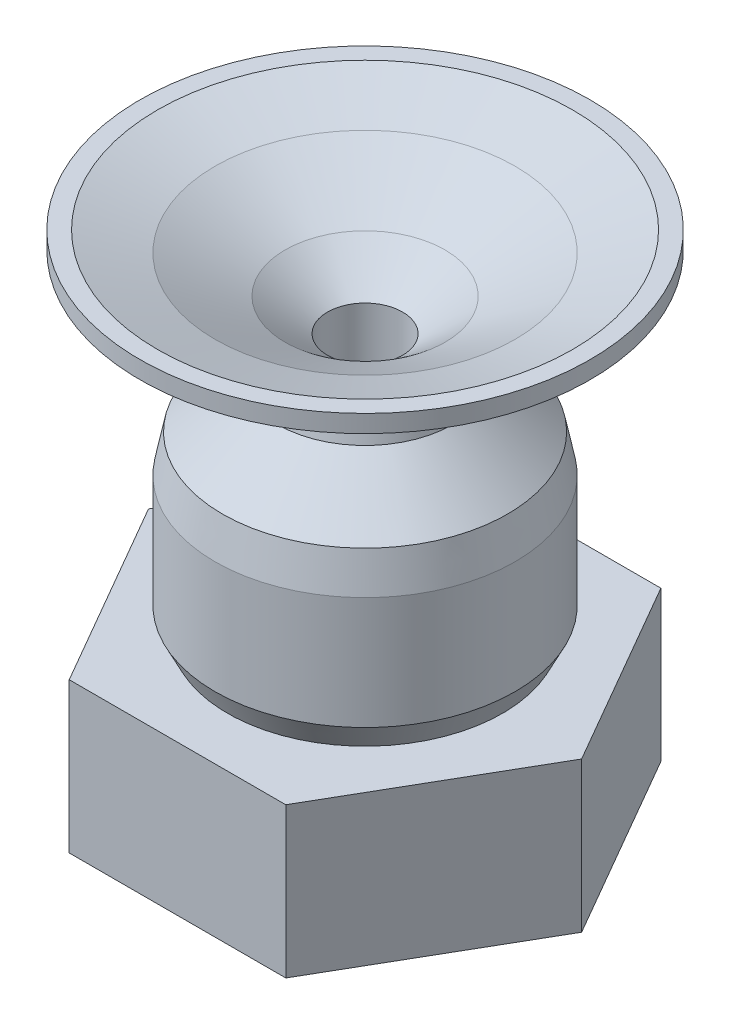
SolidWorks part; units mm, degrees
ref_plane "前基準面" through (0, 0, 0) normal (0, 0, 1) x (1, 0, 0)
ref_plane "上基準面" through (0, 0, 0) normal (0, 1, 0) x (1, 0, 0)
ref_plane "右基準面" through (0, 0, 0) normal (1, 0, 0) x (0, 0, -1)
sketch "草圖1" plane through (0, 0, 0) normal (0, 1, 0) x (1, 0, 0)
  line L0 (8.6603, 0) -> (4.3301, 7.5)
  line L1 (4.3301, 7.5) -> (-4.3301, 7.5)
  line L2 (-4.3301, 7.5) -> (-8.6603, 0)
  line L3 (-8.6603, 0) -> (-4.3301, -7.5)
  line L4 (-4.3301, -7.5) -> (4.3301, -7.5)
  line L5 (4.3301, -7.5) -> (8.6603, 0)
  circle A0 centre (0, 0) radius 1.5
extrude "六角底座_AF15_H6_通氣孔3" add sketch "草圖1" along normal blind 6
sketch "草圖2" plane through (0, 0, 0) normal (0, 0, 1) x (1, 0, 0)
  line L0 (1.5, 6) -> (5.5, 6)
  line L1 (5.5, 6) -> (6, 7)
  line L2 (6, 7) -> (6, 11.5)
  line L3 (6, 11.5) -> (5.7, 13)
  line L4 (5.7, 13) -> (3.5, 15)
  line L5 (3.5, 15) -> (3.3, 16)
  line L6 (3.3, 16) -> (4.2, 17)
  line L7 (4.2, 17) -> (6.4, 18.3)
  line L8 (6.4, 18.3) -> (9, 19.3)
  line L9 (9, 19.3) -> (9, 20)
  line L10 (9, 20) -> (8.3, 20)
  line L11 (8.3, 20) -> (6, 19.2)
  line L12 (6, 19.2) -> (3.2, 17.7)
  line L13 (3.2, 17.7) -> (1.5, 16.4)
  line L14 (1.5, 16.4) -> (1.5, 6)
  line L15 (0, 0) -> (0, 24) construction
revolve "吸盤_口徑18_H14_中空唇口" add sketch "草圖2" angle 360 about L15
